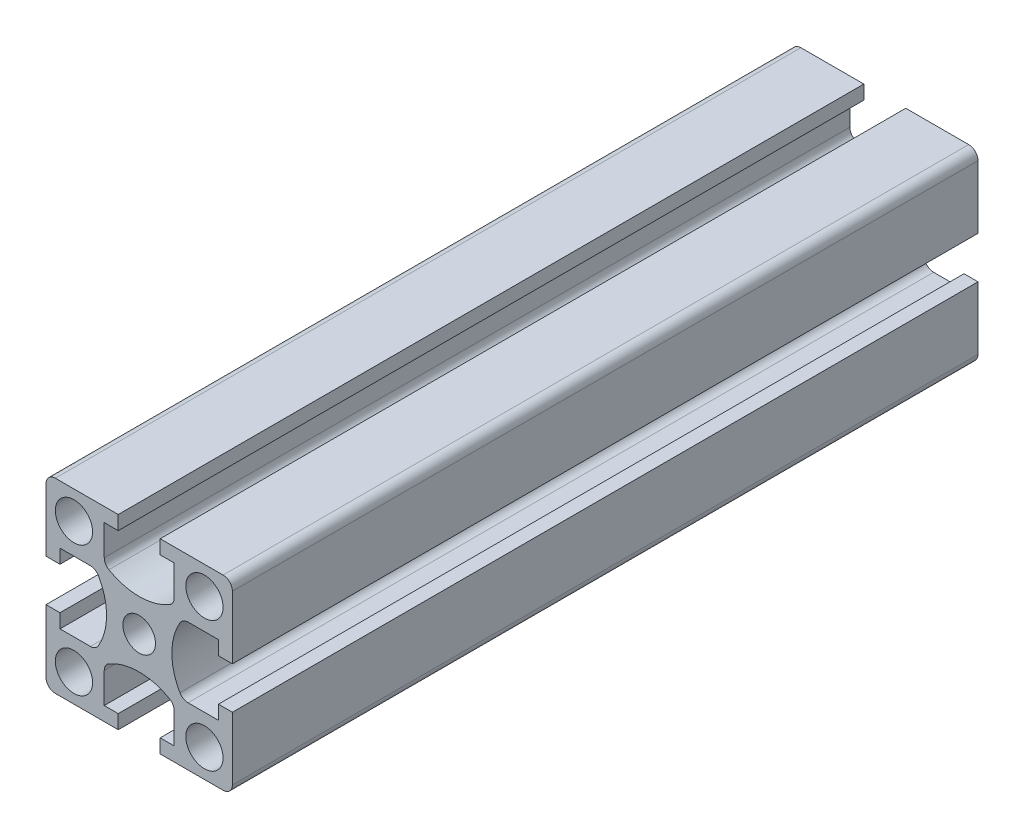
SolidWorks part; units mm, degrees
ref_plane "Front Plane" through (0, 0, 0) normal (0, 0, 1) x (1, 0, 0)
ref_plane "Top Plane" through (0, 0, 0) normal (0, 1, 0) x (1, 0, 0)
ref_plane "Right Plane" through (0, 0, 0) normal (1, 0, 0) x (0, 0, -1)
sketch "Sketch1" plane through (0, 0, 0) normal (0, 0, 1) x (1, 0, 0)
  line L64 (-12.5, 11.25) -> (-12.5, 2.8125)
  line L65 (-12.5, 2.8125) -> (-10.625, 2.8125)
  line L66 (-10.625, 2.8125) -> (-10.625, 4.6875)
  line L67 (-10.625, 4.6875) -> (-6.5461, 4.6875)
  line L68 (-6.5461, -4.6875) -> (-10.625, -4.6875)
  line L69 (-10.625, -4.6875) -> (-10.625, -2.8125)
  line L70 (-10.625, -2.8125) -> (-12.5, -2.8125)
  line L71 (-12.5, -2.8125) -> (-12.5, -11.25)
  line L72 (-11.25, -12.5) -> (-2.8125, -12.5)
  line L73 (-2.8125, -12.5) -> (-2.8125, -10.625)
  line L74 (-2.8125, -10.625) -> (-4.6875, -10.625)
  line L75 (-4.6875, -10.625) -> (-4.6875, -6.5461)
  line L76 (4.6875, -6.5461) -> (4.6875, -10.625)
  line L77 (4.6875, -10.625) -> (2.8125, -10.625)
  line L78 (2.8125, -10.625) -> (2.8125, -12.5)
  line L79 (2.8125, -12.5) -> (11.25, -12.5)
  line L80 (12.5, -11.25) -> (12.5, -2.8125)
  line L81 (12.5, -2.8125) -> (10.625, -2.8125)
  line L82 (10.625, -2.8125) -> (10.625, -4.6875)
  line L83 (10.625, -4.6875) -> (6.5461, -4.6875)
  line L84 (6.5461, 4.6875) -> (10.625, 4.6875)
  line L85 (10.625, 4.6875) -> (10.625, 2.8125)
  line L86 (10.625, 2.8125) -> (12.5, 2.8125)
  line L87 (12.5, 2.8125) -> (12.5, 11.25)
  line L88 (11.25, 12.5) -> (2.8125, 12.5)
  line L89 (2.8125, 12.5) -> (2.8125, 10.625)
  line L90 (2.8125, 10.625) -> (4.6875, 10.625)
  line L91 (4.6875, 10.625) -> (4.6875, 6.5461)
  line L92 (-4.6875, 6.5461) -> (-4.6875, 10.625)
  line L93 (-4.6875, 10.625) -> (-2.8125, 10.625)
  line L94 (-2.8125, 10.625) -> (-2.8125, 12.5)
  line L95 (-2.8125, 12.5) -> (-11.25, 12.5)
  circle A5 centre (-8.75, -8.75) radius 2.5
  circle A6 centre (8.75, -8.75) radius 2.5
  circle A7 centre (8.75, 8.75) radius 2.5
  circle A8 centre (0, 0) radius 2.1875
  circle A9 centre (-8.75, 8.75) radius 2.5
  arc A32 (-11.25, 12.5) -> (-12.5, 11.25) centre (-11.25, 11.25) ccw
  arc A33 (-5.4635, 4.0625) -> (-6.5461, 4.6875) centre (-6.5461, 3.4375) ccw
  arc A34 (-5.4635, -4.0625) -> (-5.4635, 4.0625) centre (-12.5, 0) ccw
  arc A35 (-6.5461, -4.6875) -> (-5.4635, -4.0625) centre (-6.5461, -3.4375) ccw
  arc A36 (-12.5, -11.25) -> (-11.25, -12.5) centre (-11.25, -11.25) ccw
  arc A37 (-4.0625, -5.4635) -> (-4.6875, -6.5461) centre (-3.4375, -6.5461) ccw
  arc A38 (4.0625, -5.4635) -> (-4.0625, -5.4635) centre (0, -12.5) ccw
  arc A39 (4.6875, -6.5461) -> (4.0625, -5.4635) centre (3.4375, -6.5461) ccw
  arc A40 (11.25, -12.5) -> (12.5, -11.25) centre (11.25, -11.25) ccw
  arc A41 (5.4635, -4.0625) -> (6.5461, -4.6875) centre (6.5461, -3.4375) ccw
  arc A42 (5.4635, 4.0625) -> (5.4635, -4.0625) centre (12.5, 0) ccw
  arc A43 (6.5461, 4.6875) -> (5.4635, 4.0625) centre (6.5461, 3.4375) ccw
  arc A44 (12.5, 11.25) -> (11.25, 12.5) centre (11.25, 11.25) ccw
  arc A45 (4.0625, 5.4635) -> (4.6875, 6.5461) centre (3.4375, 6.5461) ccw
  arc A46 (-4.0625, 5.4635) -> (4.0625, 5.4635) centre (0, 12.5) ccw
  arc A47 (-4.6875, 6.5461) -> (-4.0625, 5.4635) centre (-3.4375, 6.5461) ccw
extrude "Boss-Extrude1" add sketch "Sketch1" along normal blind 100
